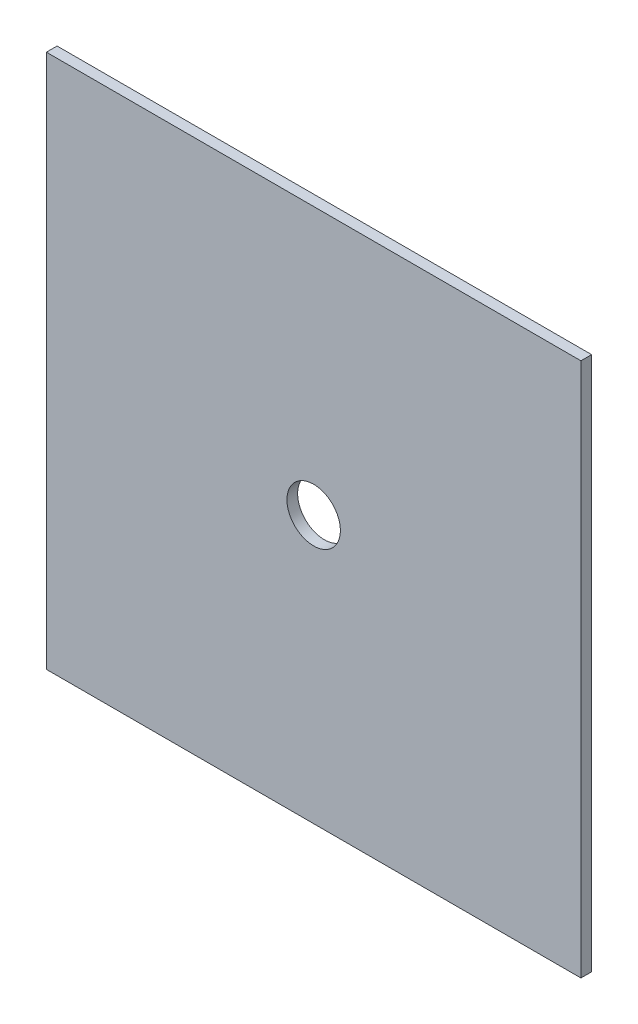
SolidWorks part; units mm, degrees
material "Ethylene-Vinyl Acetate Foam"
ref_plane "前基準面" through (0, 0, 0) normal (0, 0, 1) x (1, 0, 0)
ref_plane "上基準面" through (0, 0, 0) normal (0, 1, 0) x (1, 0, 0)
ref_plane "右基準面" through (0, 0, 0) normal (1, 0, 0) x (0, 0, -1)
sketch "草圖1" plane through (0, 0, 0) normal (0, 0, 1) x (1, 0, 0)
  line L1 (-50, 50) -> (50, 50)
  line L2 (-50, 50) -> (-50, -50)
  line L3 (-50, -50) -> (50, -50)
  line L4 (50, 50) -> (50, -50)
  line L5 (-50, 50) -> (50, -50) construction
  line L6 (-50, -50) -> (50, 50) construction
  point P0 (0, 0)
  dimension "D1" = 100
  dimension "D2" = 100
extrude "填料-伸長1" add sketch "草圖1" along normal blind 2
sketch "草圖2" plane through (0, 0, 2) normal (0, 0, 1) x (1, 0, 0)
  circle A0 centre (0, 0) radius 5
  dimension "D1" = 10
extrude "除料-伸長1" cut sketch "草圖2" against normal through all contours A0
